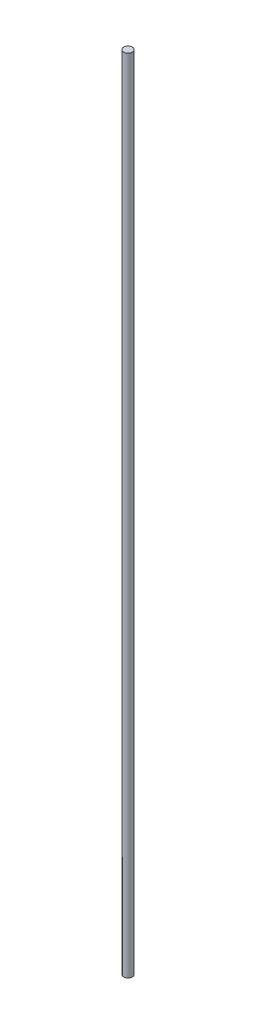
SolidWorks part; units mm, degrees
material "1060-H12 Rod (SS)"
ref_plane "Front Plane" through (0, 0, 0) normal (0, 0, 1) x (1, 0, 0)
ref_plane "Top Plane" through (0, 0, 0) normal (0, 1, 0) x (1, 0, 0)
ref_plane "Right Plane" through (0, 0, 0) normal (1, 0, 0) x (0, 0, -1)
sketch "Sketch1" plane through (0, 0, 0) normal (0, 1, 0) x (1, 0, 0)
  circle A0 centre (0, 0) radius 3
extrude "Boss-Extrude1" add sketch "Sketch1" along normal blind 550
